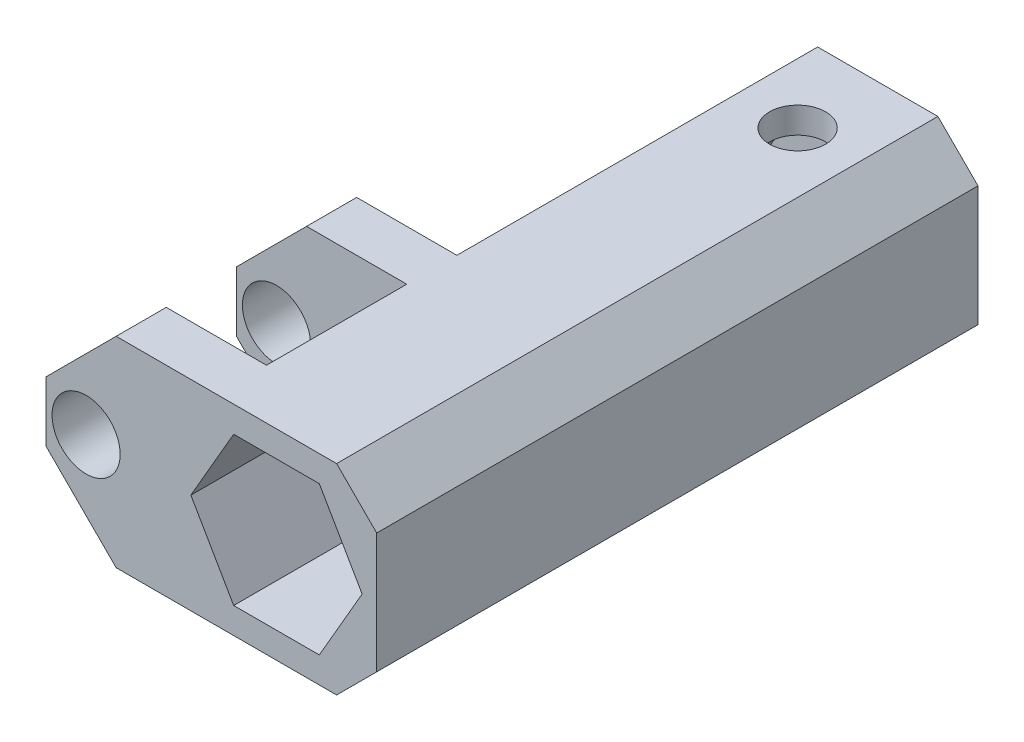
SolidWorks part; units mm, degrees
ref_plane "Plan de face" through (0, 0, 0) normal (0, 0, 1) x (1, 0, 0)
ref_plane "Plan de dessus" through (0, 0, 0) normal (0, 1, 0) x (1, 0, 0)
ref_plane "Plan de droite" through (0, 0, 0) normal (1, 0, 0) x (0, 0, -1)
sketch "Esquisse1" plane through (0, 0, 0) normal (0, 0, 1) x (1, 0, 0)
  line L1 (5, -5) -> (-5, -5)
  line L2 (5, -5) -> (5, 5)
  line L3 (5, 5) -> (-5, 5)
  line L4 (-5, -5) -> (-5, 5)
  line L5 (5, -5) -> (-5, 5) construction
  line L6 (5, 5) -> (-5, -5) construction
  point P0 (0, 0)
  dimension "D1" = 10
  dimension "D2" = 10
extrude "Boss.-Extru.1" add sketch "Esquisse1" along normal blind 30
sketch "Esquisse2" plane through (0, 0, 30) normal (0, 0, 1) x (1, 0, 0)
  line L1 (-4.2724, 0) -> (-2.1362, -3.7)
  line L2 (-2.1362, -3.7) -> (2.1362, -3.7)
  line L3 (2.1362, -3.7) -> (4.2724, 0)
  line L4 (4.2724, 0) -> (2.1362, 3.7)
  line L5 (2.1362, 3.7) -> (-2.1362, 3.7)
  line L6 (-2.1362, 3.7) -> (-4.2724, 0)
  circle A0 centre (0, 0) radius 3.7 construction
  dimension "D1" = 7.4
extrude "Enlèv. mat.-Extru.1" cut sketch "Esquisse2" against normal offset from surface (28 mm away) 2 up to face at (0, 0, 0)
sketch "Esquisse3" plane through (0, 0, 0) normal (0, 0, -1) x (-1, 0, 0)
  circle A0 centre (0, 0) radius 1.6
  dimension "D1" = 3.2
extrude "Enlèv. mat.-Extru.2" cut sketch "Esquisse3" against normal through all
sketch "Esquisse4" plane through (-5, 0, 0) normal (-1, 0, 0) x (0, 0, 1)
  line L0 (30, -5) -> (0, -5) construction
  line L1 (30, 5) -> (27.5, 5)
  line L2 (30, 5) -> (30, -5)
  line L3 (30, -5) -> (27.5, -5)
  line L4 (27.5, 5) -> (27.5, -5)
  line L5 (30, 5) -> (0, 5) construction
  line L6 (20.5, 5) -> (18, 5)
  line L7 (20.5, 5) -> (20.5, -5)
  line L8 (20.5, -5) -> (18, -5)
  line L9 (18, 5) -> (18, -5)
  dimension "D1" = 2.5
  dimension "D2" = 2.5
  dimension "D3" = 7
extrude "Boss.-Extru.2" add sketch "Esquisse4" along normal blind 6.5
chamfer "Chanfrein2" distance 3.5 angle 45 4 edges at (-11.5, -5, 28.75) (-11.5, 5, 28.75) (-11.5, -5, 19.25) (-11.5, 5, 19.25)
sketch "Esquisse5" plane through (0, 0, 18) normal (0, 0, -1) x (-1, 0, 0)
  line L0 (11.5, 1.5) -> (11.5, -1.5) construction
  line L2 (9.075, 0) -> (-9.075, 0) construction
  circle A0 centre (9.5, 0) radius 1.7
  point P2 (11.5, 0)
  dimension "D3" = 3.4
  dimension "D1" = 2
  dimension "D2" = 0
extrude "Enlèv. mat.-Extru.3" cut sketch "Esquisse5" against normal through all
ref_plane "Plan1" through (0, 0, 24) normal (0, 0, -1) x (-1, 0, 0)
chamfer "Chanfrein3" distance 2 angle 45 6 edges at (5, -5, 15) (5, 5, 15)
sketch "Esquisse9" plane through (0, 5, 0) normal (0, 1, 0) x (1, 0, 0)
  line L0 (3, 0) -> (-3, 0) construction
  circle A0 centre (0, -4) radius 1.4
  point P2 (0, 0)
  dimension "D1" = 2.8
  dimension "D2" = 4
extrude "Enlèv. mat.-Extru.4" cut sketch "Esquisse9" against normal blind 10
equation "\"¨3.4\"=3.3"
